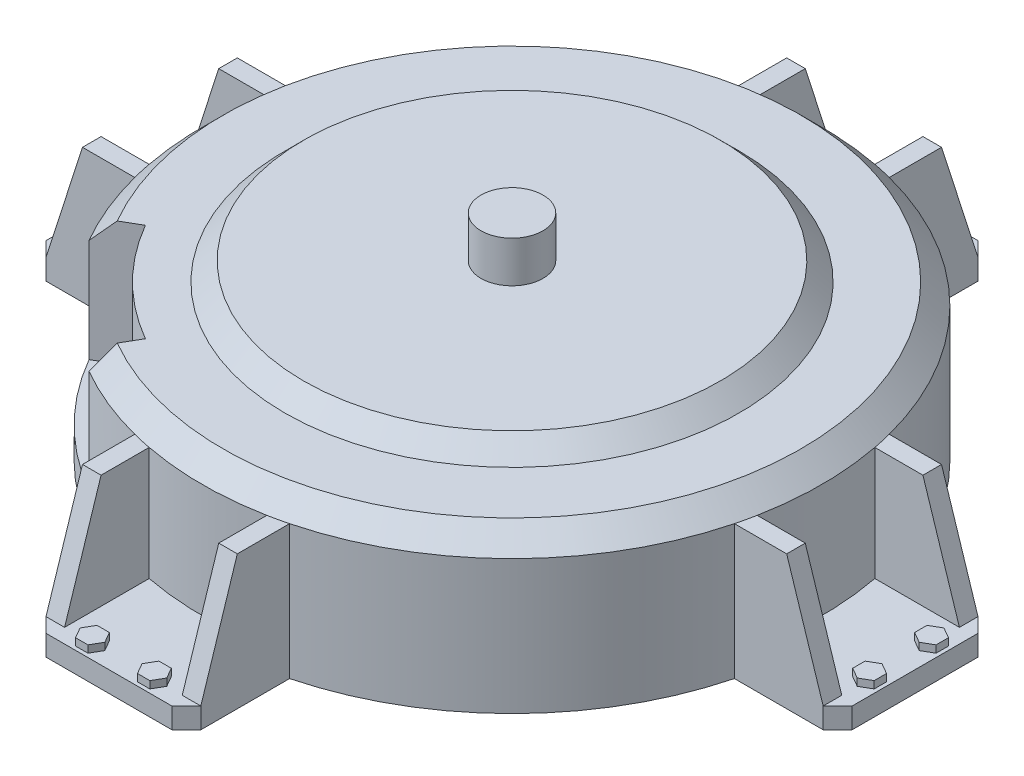
SolidWorks part; units mm, degrees
ref_plane "Front Plane" through (0, 0, 0) normal (0, 0, 1) x (1, 0, 0)
ref_plane "Top Plane" through (0, 0, 0) normal (0, 1, 0) x (1, 0, 0)
ref_plane "Right Plane" through (0, 0, 0) normal (1, 0, 0) x (0, 0, -1)
sketch "Sketch1" plane through (0, 0, 0) normal (0, 1, 0) x (1, 0, 0)
  circle A0 centre (0, 0) radius 150
  dimension "D1" = 300
extrude "Boss-Extrude1" add sketch "Sketch1" along normal blind 75
chamfer "Chamfer1" distance 10 angle 45 1 edges at (0, 75, 150)
sketch "Sketch2" plane through (0, 0, 0) normal (0, -1, 0) x (1, 0, 0)
  line L0 (0, 0) -> (150, 0) construction
  line L1 (145.2369, 37.5) -> (195.2369, 37.5)
  line L2 (145.2369, -37.5) -> (195.2369, -37.5)
  line L3 (195.2369, 37.5) -> (195.2369, -37.5)
  circle A0 centre (0, 0) radius 150 construction
  circle A2 centre (0, 0) radius 150
  arc A3 (145.2369, -37.5) -> (145.2369, 37.5) centre (0, 0) ccw
  dimension "D1" = 50
  dimension "D2" = 75
  dimension "D3" = 0
extrude "Boss-Extrude2" add sketch "Sketch2" against normal blind 10
chamfer "Chamfer2" distance 7 angle 45 2 edges at (195.2369, 5, 37.5) (195.2369, 5, -37.5)
sketch "Sketch3" plane through (0, 0, -37.5) normal (0, 0, -1) x (-1, 0, 0)
  line L0 (-145.2369, 10) -> (-145.2369, 65)
  line L1 (150, 65) -> (-150, 65) construction
  line L2 (-145.2369, 65) -> (-170.5569, 65)
  line L3 (-170.5569, 65) -> (-188.2369, 10)
  line L4 (-188.2369, 10) -> (-145.2369, 10)
  dimension "D1" = 17.68
extrude "Boss-Extrude3" add sketch "Sketch3" against normal blind 9
sketch "Sketch4" plane through (0, 10, 0) normal (0, 1, 0) x (1, 0, 0)
  line L0 (188.2369, 37.5) -> (188.2369, -37.5) construction
  line L2 (188.2369, 21) -> (183.0407, 18)
  line L3 (183.0407, 18) -> (183.0407, 12)
  line L4 (183.0407, 12) -> (188.2369, 9)
  line L5 (188.2369, 9) -> (193.433, 12)
  line L6 (193.433, 12) -> (193.433, 18)
  line L7 (193.433, 18) -> (188.2369, 21)
  circle A0 centre (188.2369, 15) radius 5.1962 construction
  dimension "D1" = 6
  dimension "D2" = 13.5
extrude "Boss-Extrude4" add sketch "Sketch4" along normal blind 3.5
mirror "Mirror1" about plane through (0, 0, 0) normal (0, 0, 1) of "Boss-Extrude3", "Boss-Extrude4"
pattern_circular "CirPattern1" count 4 over 360 about axis through (0, 0, 0) along (0, 1, 0) of "Boss-Extrude2", "Chamfer2", "Boss-Extrude3", "Boss-Extrude4", "Mirror1"
sketch "Sketch5" plane through (0, 75, 0) normal (0, 1, 0) x (1, 0, 0)
  circle A0 centre (0, 0) radius 110
  dimension "D1" = 220
extrude "Boss-Extrude5" add sketch "Sketch5" along normal blind 9 draft 45
sketch "Sketch6" plane through (0, 75, 0) normal (0, 1, 0) x (1, 0, 0)
  line L0 (-130, 0) -> (-232.002, 0) construction
  line L1 (-112.5833, -65) -> (-129.9038, -75)
  line L2 (-65, -112.5833) -> (-75, -129.9038)
  arc A0 (-145.2369, -37.5) -> (-37.5, -145.2369) centre (0, 0) ccw construction
  arc A1 (-129.9038, -75) -> (-75, -129.9038) centre (0, 0) ccw
  arc A2 (-112.5833, -65) -> (-65, -112.5833) centre (0, 0) ccw
  dimension "D3" = 260
  dimension "D1" = 30
  dimension "D2" = 30
extrude "Cut-Extrude1" cut sketch "Sketch6" against normal blind 60
sketch "Sketch7" plane through (0, 84, 0) normal (0, 1, 0) x (1, 0, 0)
  circle A0 centre (0, 0) radius 15
  dimension "D1" = 30
extrude "Boss-Extrude6" add sketch "Sketch7" along normal blind 20
sketch "Sketch8" plane through (0, 0, 0) normal (0, -1, 0) x (1, 0, 0)
  circle A0 centre (0, 0) radius 27.5
  dimension "D1" = 55
extrude "Cut-Extrude2" cut sketch "Sketch8" against normal blind 60
